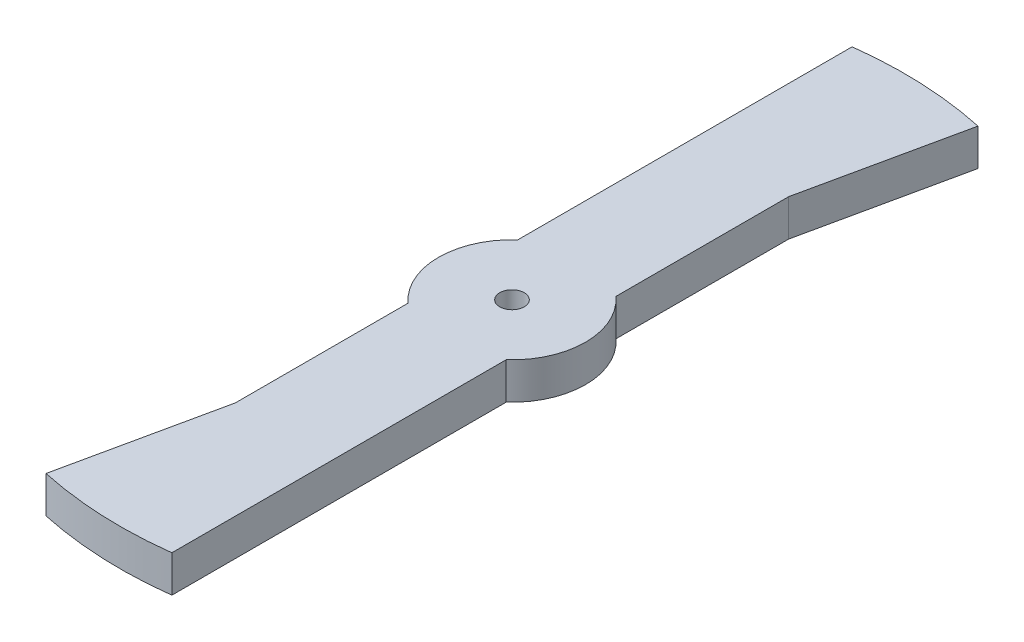
SolidWorks part; units mm, degrees
material "AISI 316 Stainless Steel Sheet (SS)"
ref_plane "Front Plane" through (0, 0, 0) normal (0, 0, 1) x (1, 0, 0)
ref_plane "Top Plane" through (0, 0, 0) normal (0, 1, 0) x (1, 0, 0)
ref_plane "Right Plane" through (0, 0, 0) normal (1, 0, 0) x (0, 0, -1)
sketch "Sketch1" plane through (0, 0, 0) normal (0, 1, 0) x (1, 0, 0)
  line L0 (0, 19.05) -> (0, 101.6) construction
  line L1 (-12.7, 100.8031) -> (-12.7, 14.199)
  line L2 (12.7, 14.199) -> (12.7, 58.973)
  line L3 (12.7, 58.973) -> (21.3895, 99.323)
  line L4 (12.7, -100.8031) -> (12.7, -14.199)
  line L5 (-12.7, -58.973) -> (-21.3895, -99.323)
  line L6 (-12.7, -14.199) -> (-12.7, -58.973)
  circle A0 centre (0, 0) radius 3.175
  circle A1 centre (0, 0) radius 19.05 construction
  circle A2 centre (0, 0) radius 101.6 construction
  arc A3 (-12.7, 100.8031) -> (21.3895, 99.323) centre (0, 0) cw
  circle A4 centre (0, 0) radius 60.325 construction
  arc A5 (12.7, -100.8031) -> (-21.3895, -99.323) centre (0, 0) cw
  arc A6 (-12.7, 14.199) -> (-12.7, -14.199) centre (0, 0) ccw
  arc A7 (12.7, 14.199) -> (12.7, -14.199) centre (0, 0) cw
  point P9 (12.7, 14.199)
  point P15 (0, 60.325)
  point P23 (0, 0)
  dimension "D1" = 6.35
  dimension "D2" = 38.1
  dimension "D3" = 203.2
  dimension "D5" = 12.7
  dimension "D4" = 12.7
  dimension "D6" = 2
extrude "Boss-Extrude1" add sketch "Sketch1" along normal blind 9.525 contours A7 L2 L3 A3 L1 A6 L6 L5 A5 L4 A0
